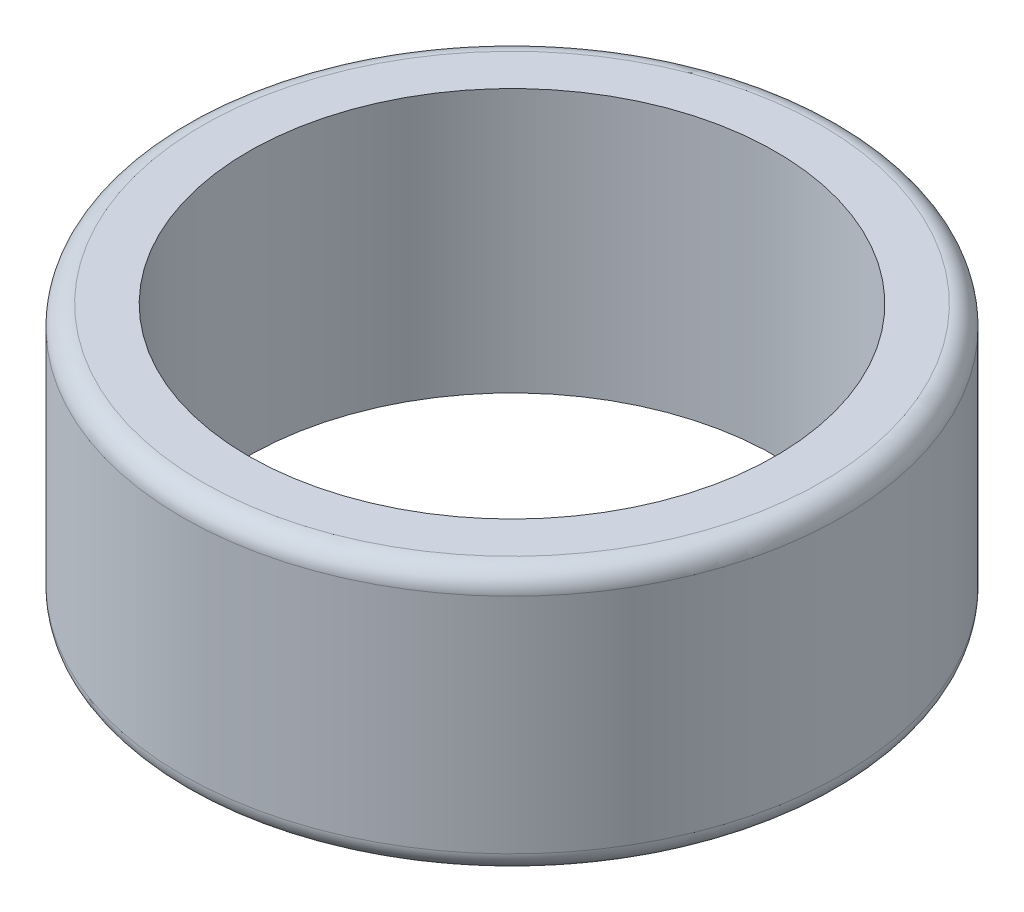
SolidWorks part; units mm, degrees
ref_plane "前视基准面" through (0, 0, 0) normal (0, 0, 1) x (1, 0, 0)
ref_plane "上视基准面" through (0, 0, 0) normal (0, 1, 0) x (1, 0, 0)
ref_plane "右视基准面" through (0, 0, 0) normal (1, 0, 0) x (0, 0, -1)
sketch "草图1" plane through (0, 0, 0) normal (0, 1, 0) x (1, 0, 0)
  circle A0 centre (0, 0) radius 32.5
  dimension "D1" = 65
extrude "凸台-拉伸1" add sketch "草图1" along normal blind 26
ref_plane "基准面1" through (0, 16, 0) normal (0, 1, 0) x (1, 0, 0)
sketch "草图3" plane through (0, 26, 0) normal (0, 1, 0) x (1, 0, 0)
  circle A0 centre (0, 0) radius 26
  dimension "D1" = 52
extrude "切除-拉伸1" cut sketch "草图3" against normal through all
fillet "圆角1" radius 2 2 edges at (0, 0, 32.5) (0, 26, 32.5)
